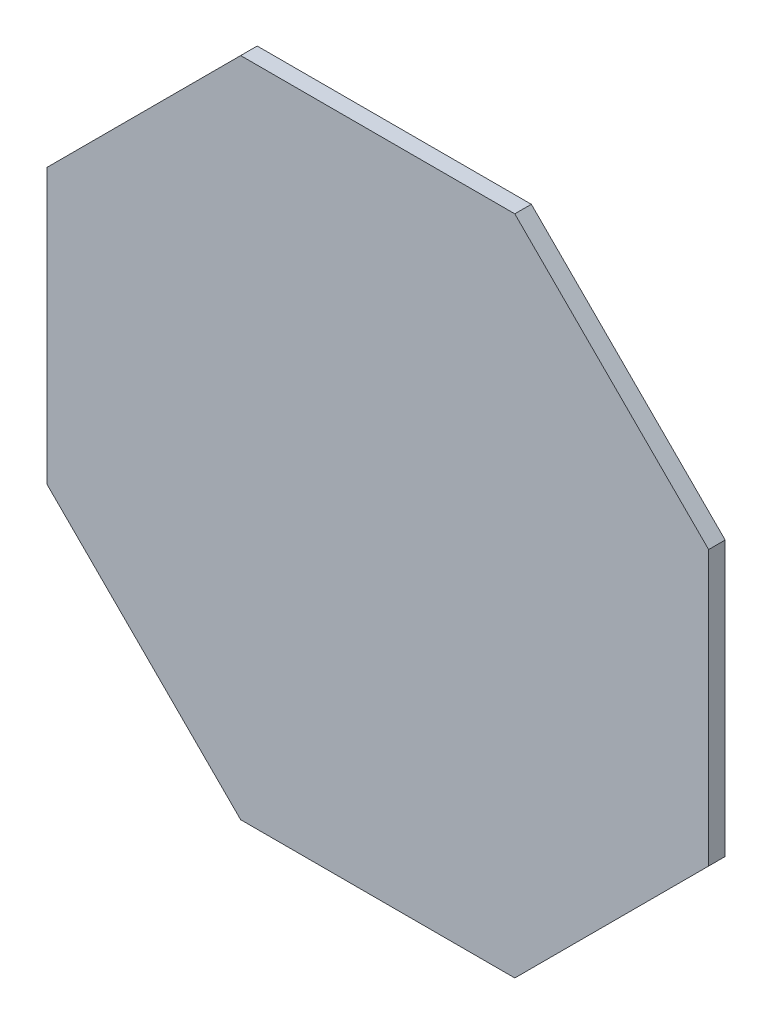
SolidWorks part; units mm, degrees
ref_plane "Plan de face" through (0, 0, 0) normal (0, 0, 1) x (1, 0, 0)
ref_plane "Plan de dessus" through (0, 0, 0) normal (0, 1, 0) x (1, 0, 0)
ref_plane "Plan de droite" through (0, 0, 0) normal (1, 0, 0) x (0, 0, -1)
sketch "Esquisse1" plane through (0, 0, 0) normal (0, 0, 1) x (1, 0, 0)
  line L0 (16.5685, -40) -> (40, -16.5685)
  line L1 (40, 16.5685) -> (16.5685, 40)
  line L2 (16.5685, 40) -> (-16.5685, 40)
  line L3 (-16.5685, 40) -> (-40, 16.5685)
  line L4 (-40, 16.5685) -> (-40, -16.5685)
  line L5 (-40, -16.5685) -> (-16.5685, -40)
  line L6 (-16.5685, -40) -> (16.5685, -40)
  line L7 (40, -16.5685) -> (40, 16.5685)
  line L8 (0, -55) -> (0, 55) construction
  circle A0 centre (0, 0) radius 40 construction
  dimension "D1" = 80
extrude "Boss.-Extru.1" add sketch "Esquisse1" along normal blind 2
sketch "Esquisse3" plane through (0, -40, 0) normal (0, -1, 0) x (1, 0, 0)
  line L1 (0, -55) -> (0, 55) construction
  line L2 (7.2, 1.9) -> (-7.2, 1.9)
  line L3 (7.2, 1.9) -> (7.2, -6.5)
  line L4 (7.2, -6.5) -> (-7.2, -6.5)
  line L5 (-7.2, 1.9) -> (-7.2, -6.5)
  line L8 (5.2, -0.1) -> (-5.2, -0.1)
  line L9 (5.2, -0.1) -> (5.2, -4.5)
  line L10 (5.2, -4.5) -> (-5.2, -4.5)
  line L11 (-5.2, -0.1) -> (-5.2, -4.5)
  line L12 (5.2, -0.1) -> (-5.2, -4.5) construction
  line L13 (5.2, -4.5) -> (-5.2, -0.1) construction
  line L16 (-16.5685, 2) -> (16.5685, 2) construction
  point P0 (0, 1.9)
  point P9 (0, -2.3)
  point P15 (-7.2, -2.3)
  dimension "D1" = 14.4
  dimension "D2" = 8.4
  dimension "D3" = 2
  dimension "D4" = 2
  dimension "D5" = 0.1
extrude "Boss.-Extru.3" add sketch "Esquisse3" against normal blind 15
draft "Dépouille3" type of draft neutral plane draft angle 2 faces to draft 4 face at (0, -32.5, -0.1) face at (-5.2, -32.5, -2.3) face at (0, -32.5, -4.5) face at (5.2, -32.5, -2.3) neutral plane through (-16.5685, -40, 2) neutral plane normal (0, -1, 0) parameters "D1"=2
ref_plane "Plan1" through (0, 0, -2.3) normal (0, 0, 1) x (1, 0, 0)
